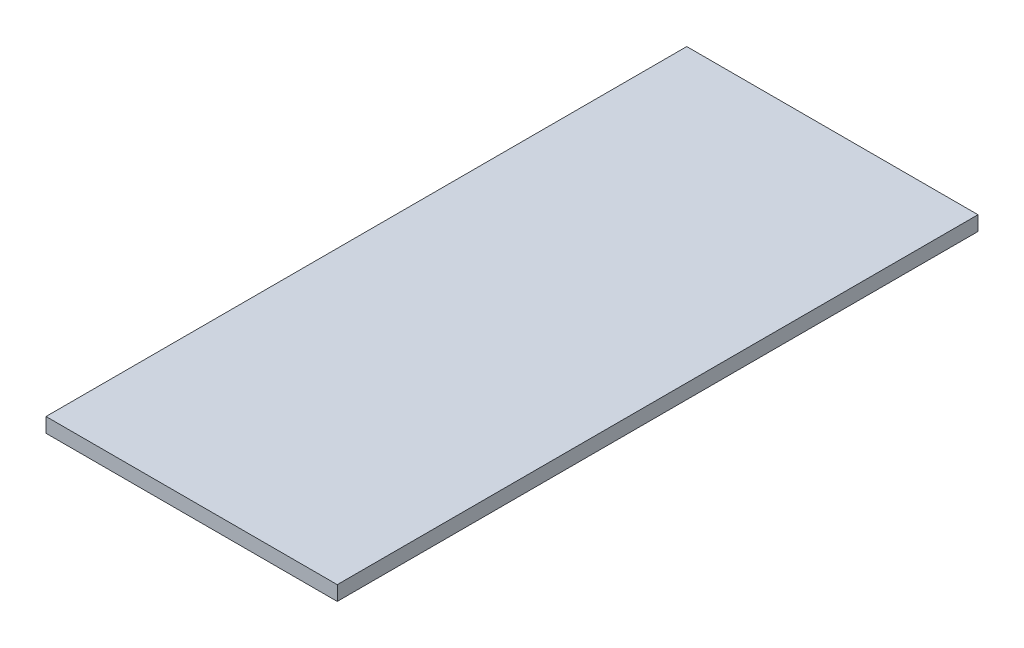
SolidWorks part; units mm, degrees
ref_plane "Front Plane" through (0, 0, 0) normal (0, 0, 1) x (1, 0, 0)
ref_plane "Top Plane" through (0, 0, 0) normal (0, 1, 0) x (1, 0, 0)
ref_plane "Right Plane" through (0, 0, 0) normal (1, 0, 0) x (0, 0, -1)
sketch "Sketch1" plane through (0, 0, 0) normal (0, 1, 0) x (1, 0, 0)
  line L1 (-127, -279.4) -> (127, -279.4)
  line L2 (-127, -279.4) -> (-127, 279.4)
  line L3 (-127, 279.4) -> (127, 279.4)
  line L4 (127, -279.4) -> (127, 279.4)
  line L5 (-127, -279.4) -> (127, 279.4) construction
  line L6 (-127, 279.4) -> (127, -279.4) construction
  point P0 (0, 0)
  dimension "D1" = 558.8
  dimension "D2" = 254
extrude "Boss-Extrude1" add sketch "Sketch1" along normal blind 12.7
